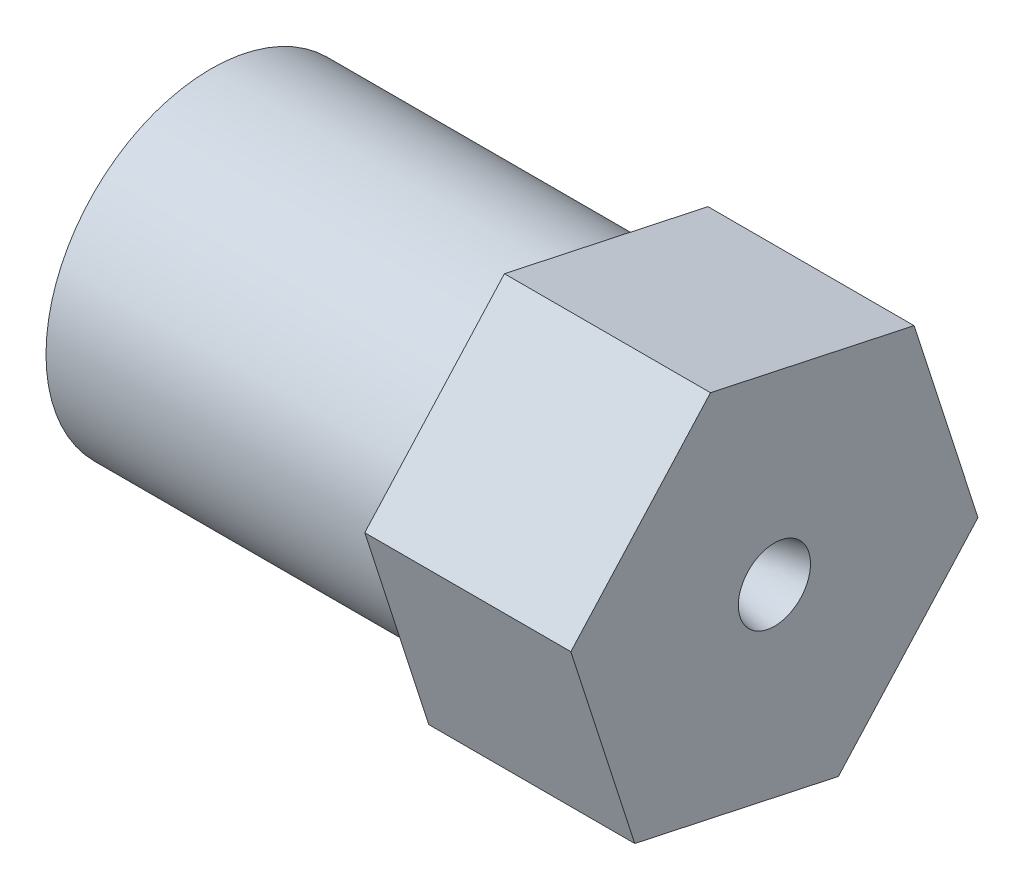
SolidWorks part; units mm, degrees
ref_plane "Front Plane" through (0, 0, 0) normal (0, 0, 1) x (1, 0, 0)
ref_plane "Top Plane" through (0, 0, 0) normal (0, 1, 0) x (1, 0, 0)
ref_plane "Right Plane" through (0, 0, 0) normal (1, 0, 0) x (0, 0, -1)
sketch "Sketch1" plane through (0, 0, 0) normal (0, 0, 1) x (1, 0, 0)
  line L0 (0, 0) -> (2.9811, 0) construction
  line L1 (0.2052, 1.5362) -> (2.9811, 2.5465) construction
  line L2 (-1.591, 2.159) -> (-2.947, 3.5151)
  line L3 (-31.75, 4.445) -> (-31.75, 10.16) construction
  line L4 (-5.1921, 4.445) -> (-31.75, 4.445) construction
  line L5 (-31.75, 10.16) -> (-9.7189, 10.16)
  line L6 (2.9811, 10.16) -> (2.9811, 2.2249)
  line L7 (2.9811, 2.2249) -> (13.0682, 3.6425) construction
  line L8 (-9.7189, 10.16) -> (2.9811, 10.16)
  line L9 (-5.1921, 4.445) -> (-13.462, 4.445)
  line L10 (-19.939, 5.461) -> (-19.939, 6.8199)
  line L11 (-20.066, 6.9469) -> (-24.892, 6.9469)
  line L12 (-24.892, 6.9469) -> (-24.892, 7.8994)
  line L13 (-25.019, 8.0264) -> (-31.115, 8.0264)
  line L14 (-31.75, 10.16) -> (-31.75, 8.6614)
  line L15 (0, 0) -> (-31.75, 0) construction
  line L16 (-13.462, 4.445) -> (-13.462, 4.699)
  line L17 (-13.589, 4.826) -> (-19.304, 4.826)
  arc A0 (-1.591, 2.159) -> (0, 1.5) centre (0, 3.75) ccw
  arc A1 (0, 1.5) -> (0.2052, 1.5362) centre (0, 2.1) ccw
  arc A2 (-2.947, 3.5151) -> (-5.1921, 4.445) centre (-5.1921, 1.27) ccw
  arc A3 (-31.115, 8.0264) -> (-31.75, 8.6614) centre (-31.115, 8.6614) cw
  arc A4 (-19.304, 4.826) -> (-19.939, 5.461) centre (-19.304, 5.461) cw
  arc A5 (-13.462, 4.699) -> (-13.589, 4.826) centre (-13.589, 4.699) ccw
  arc A6 (-19.939, 6.8199) -> (-20.066, 6.9469) centre (-20.066, 6.8199) ccw
  arc A7 (-24.892, 7.8994) -> (-25.019, 8.0264) centre (-25.019, 7.8994) ccw
  parabola Q0 (2.9811, 2.2249) -> (0.2052, 1.5362) focus (2.4933, -4.7503) apex (0.2052, 1.5362)
  point P30 (-31.75, 8.0264)
  point P39 (-24.892, 8.0264)
  dimension "D3" = 2.25
  dimension "D4" = 0.6
  dimension "D11" = 3.175
  dimension "D12" = 8
  dimension "D14" = 6.9469
  dimension "D20" = 0.635
  dimension "D21" = 0.127
  dimension "D2" = 2.9811
  dimension "D5" = 2.2249
  dimension "D6" = 20
  dimension "D7" = 45
  dimension "D8" = 8.0264
  dimension "D9" = 31.75
  dimension "D10" = 10.16
  dimension "D13" = 12.7
  dimension "D15" = 4.445
  dimension "D16" = 6.858
  dimension "D17" = 11.811
  dimension "D18" = 18.288
  dimension "D19" = 4.826
  dimension "D22" = 1.5
revolve "Revolve1" add sketch "Sketch1" angle 360 about L0
sketch "Sketch4" plane through (2.9811, 0, 0) normal (1, 0, 0) x (0, 0, -1)
  line L1 (3.9404, -12.2116) -> (12.5458, -2.6933)
  line L2 (12.5458, -2.6933) -> (8.6054, 9.5183)
  line L3 (8.6054, 9.5183) -> (-3.9404, 12.2116)
  line L4 (-3.9404, 12.2116) -> (-12.5458, 2.6933)
  line L5 (-12.5458, 2.6933) -> (-8.6054, -9.5183)
  line L6 (-8.6054, -9.5183) -> (3.9404, -12.2116)
  circle A0 centre (0, 0) radius 10.16
  circle A1 centre (0, 0) radius 10.16 construction
  circle A2 centre (0, 0) radius 11.1125 construction
  circle M1 centre (0, 0) radius 10.16
  dimension "D1" = 22.225
extrude "Boss-Extrude1" add sketch "Sketch4" against normal blind 12.7 contours L4 L5 M1 | L3 L4 M1 | L2 L3 M1 | L1 L2 M1 | L6 L1 M1 | L5 L6 M1
fillet "Fillet1" radius 0.635 1 edges at (-9.7189, 0, -10.16)
equation "\"D3@Sketch1\" = 1.5 * \"D22@Sketch1\""
equation "\"D4@Sketch1\"  = .4 * \"D22@Sketch1\""
equation "\"D5@Sketch1\"=\"D22@Sketch1\" * ( \"er\") ^ .5"
equation "\"er\" = 2.2"
